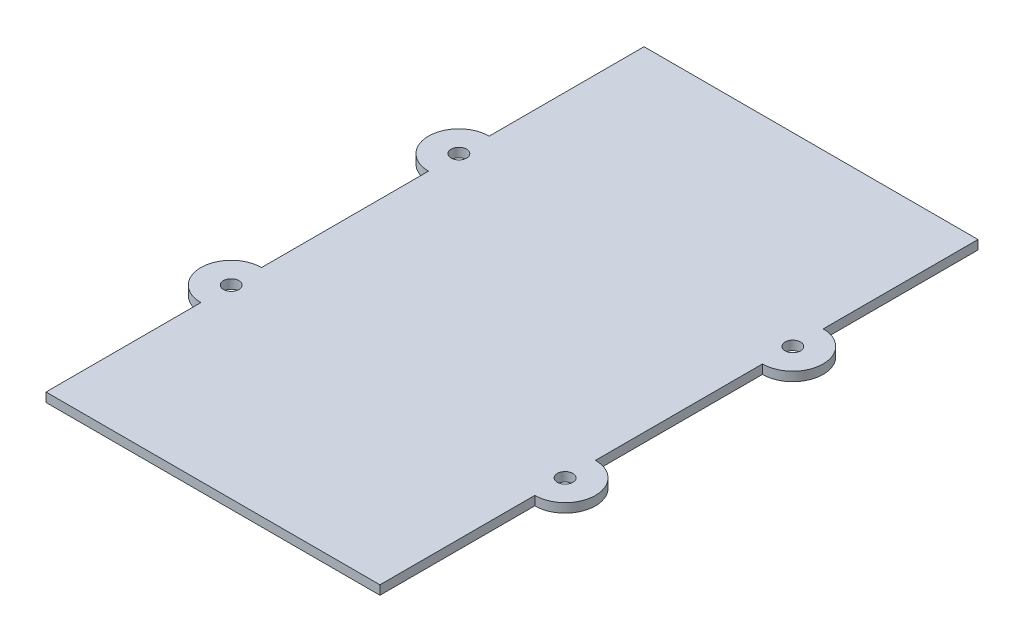
SolidWorks part; units mm, degrees
material "CF-ntbk"
ref_plane "Front Plane" through (0, 0, 0) normal (0, 0, 1) x (1, 0, 0)
ref_plane "Top Plane" through (0, 0, 0) normal (0, 1, 0) x (1, 0, 0)
ref_plane "Right Plane" through (0, 0, 0) normal (1, 0, 0) x (0, 0, -1)
sketch "Sketch1" plane through (0, 0, 0) normal (0, 1, 0) x (1, 0, 0)
  line L0 (-55, 27.5) -> (-55, -27.5)
  line L2 (55, 27.5) -> (55, -27.5)
  line L4 (-44.2539, 0) -> (44.2539, 0) construction
  line L5 (-55, 47.5) -> (-55, 98.5)
  line L6 (0, -44.7868) -> (0, 44.7868) construction
  line L7 (-55, 98.5) -> (55, 98.5)
  line L8 (55, 98.5) -> (55, 47.5)
  line L9 (-55, -47.5) -> (-55, -98.5)
  line L10 (-55, -98.5) -> (55, -98.5)
  line L11 (55, -47.5) -> (55, -98.5)
  arc A0 (-55, 47.5) -> (-55, 27.5) centre (-55, 37.5) ccw
  arc A1 (55, 47.5) -> (55, 27.5) centre (55, 37.5) cw
  arc A2 (55, -27.5) -> (55, -47.5) centre (55, -37.5) cw
  arc A3 (-55, -27.5) -> (-55, -47.5) centre (-55, -37.5) ccw
  circle A4 centre (-55, 37.5) radius 2.55
  circle A5 centre (55, 37.5) radius 2.55
  circle A6 centre (-55, -37.5) radius 2.55
  circle A7 centre (55, -37.5) radius 2.55
  dimension "D1" = 5.1
  dimension "D2" = 10
  dimension "D3" = 55
  dimension "D5" = 110
  dimension "D6" = 110
  dimension "D7" = 55
  dimension "D4" = 37.5
  dimension "D8" = 197
  dimension "D9" = 110
extrude "Boss-Extrude1" add sketch "Sketch1" along normal blind 3
sketch "ConstructionLines" plane through (0, 3, 0) normal (0, 1, 0) x (1, 0, 0)
  line L0 (-52, 91) -> (-52, -91)
  line L1 (-52, -91) -> (52, -91)
  line L2 (52, -91) -> (52, 91)
  line L3 (52, 91) -> (-52, 91)
  line L5 (0, 91) -> (0, -91)
  line L6 (0, -44.7868) -> (0, 44.7868) construction
  line L7 (-52, 0) -> (52, 0)
  line L9 (-44.2539, 0) -> (44.2539, 0) construction
  dimension "D1" = 182
  dimension "D2" = 104
  dimension "D4" = 52
  dimension "D3" = 91
equation "\"ThreadHoleSize\"=5.1"
equation "\"D1@Sketch1\"=\"ThreadHoleSize\""
equation "\"HoleAreaSize\"= 10"
equation "\"D2@Sketch1\"=\"HoleAreaSize\""
equation "\"MidLength\"=172"
equation "\"HoleDist\"=55"
equation "\"D3@Sketch1\"=\"HoleDist\""
equation "\"Width\"=110"
equation "\"D6@Sketch1\"=\"Width\""
equation "\"D5@Sketch1\"=\"Width\""
equation "\"D7@Sketch1\"=\"Width\"/2"
equation "\"BatWidth\"=52"
equation "\"D4@ConstructionLines\" = \"BatWidth\""
equation "\"BatLength\"=182"
equation "\"D1@ConstructionLines\"=\"BatLength\""
equation "\"D3@ConstructionLines\"=\"BatLength\"/2"
equation "\"D4@Sketch1\"=\"HoleDist\"/2 +\"HoleAreaSize\""
equation "\"D8@Sketch1\"=\"BatLength\" + 15"
equation "\"D9@Sketch1\"=\"Width\""
